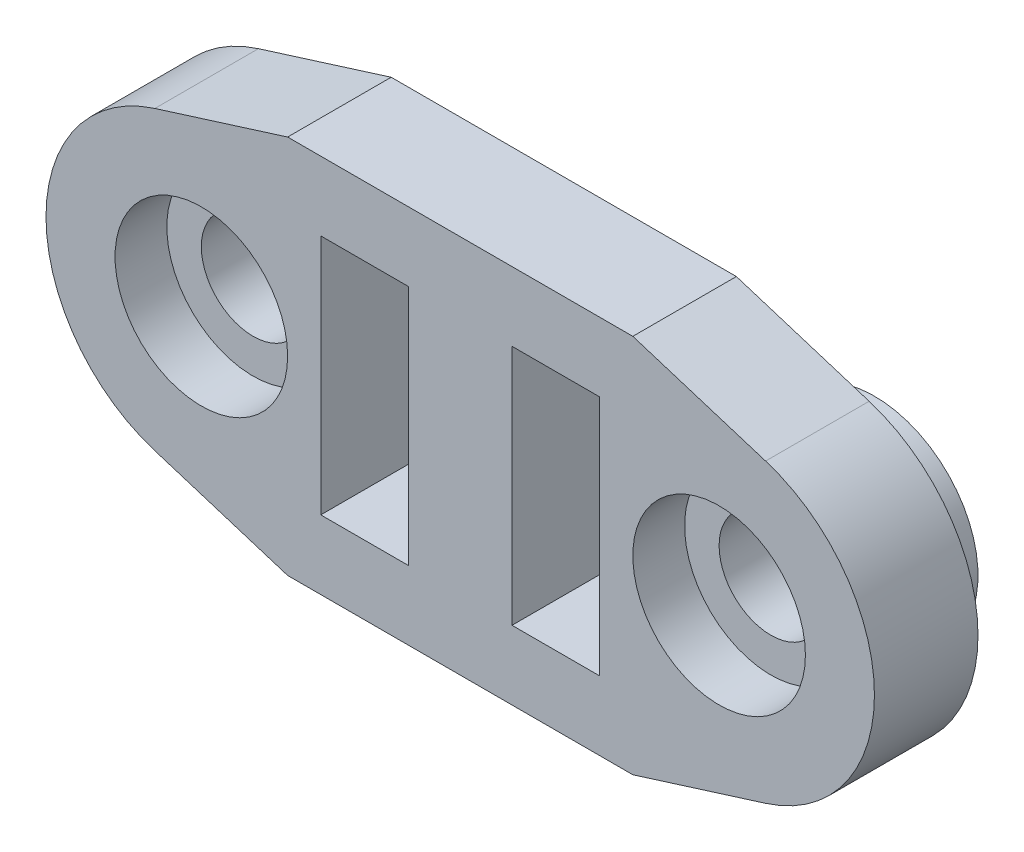
SolidWorks part; units mm, degrees
material "PLA"
ref_plane "Front Plane" through (0, 0, 0) normal (0, 0, 1) x (1, 0, 0)
ref_plane "Top Plane" through (0, 0, 0) normal (0, 1, 0) x (1, 0, 0)
ref_plane "Right Plane" through (0, 0, 0) normal (1, 0, 0) x (0, 0, -1)
sketch "Sketch1" plane through (0, 0, 0) normal (0, 0, 1) x (1, 0, 0)
  line L0 (-5, 5.5) -> (5, 5.5)
  line L1 (5, 5.5) -> (8.8465, 4.2938)
  line L2 (8.8465, -4.2938) -> (5, -5.5)
  line L3 (5, -5.5) -> (-5, -5.5)
  line L4 (-5, -5.5) -> (-8.8465, -4.2938)
  line L5 (-8.8465, 4.2938) -> (-5, 5.5)
  arc A0 (8.8465, 4.2938) -> (8.8465, -4.2938) centre (7.5, 0) cw
  arc A1 (-8.8465, -4.2938) -> (-8.8465, 4.2938) centre (-7.5, 0) cw
  circle A2 centre (-7.5, 0) radius 1.5
  circle A3 centre (7.5, 0) radius 1.5
  point P11 (0, -5.5)
  dimension "D3" = 4.5
  dimension "D4" = 3
  dimension "D1" = 11
  dimension "D2" = 15
  dimension "D5" = 10
extrude "Boss-Extrude1" add sketch "Sketch1" along normal mid plane 3
sketch "Sketch2" plane through (0, 0, -1.5) normal (0, 0, -1) x (-1, 0, 0)
  circle A0 centre (-7.5, 0) radius 3
  circle A1 centre (-7.5, 0) radius 1.5
  circle A2 centre (7.5, 0) radius 3
  circle A3 centre (7.5, 0) radius 1.5
  circle A4 centre (-7.5, 0) radius 1.5 construction
  circle A5 centre (7.5, 0) radius 1.5 construction
  dimension "D1" = 6
extrude "Boss-Extrude2" add sketch "Sketch2" along normal blind 1.5
sketch "Sketch3" plane through (0, 0, 1.5) normal (0, 0, 1) x (1, 0, 0)
  circle A0 centre (-7.5, 0) radius 2.5
  circle A1 centre (7.5, 0) radius 2.5
  dimension "D1" = 5
extrude "Cut-Extrude1" cut sketch "Sketch3" against normal blind 1.5
sketch "Sketch4" plane through (0, 0, 1.5) normal (0, 0, 1) x (1, 0, 0)
  line L0 (-1.5, 0) -> (1.5, 0) construction
  line L1 (-4.04, -3.5) -> (-1.5, -3.5)
  line L2 (-4.04, -3.5) -> (-4.04, 3.5)
  line L3 (-4.04, 3.5) -> (-1.5, 3.5)
  line L4 (-1.5, -3.5) -> (-1.5, 3.5)
  line L5 (-4.04, -3.5) -> (-1.5, 3.5) construction
  line L6 (-4.04, 3.5) -> (-1.5, -3.5) construction
  line L7 (1.5, -3.5) -> (4.04, -3.5)
  line L8 (1.5, -3.5) -> (1.5, 3.5)
  line L9 (1.5, 3.5) -> (4.04, 3.5)
  line L10 (4.04, -3.5) -> (4.04, 3.5)
  line L11 (1.5, -3.5) -> (4.04, 3.5) construction
  line L12 (1.5, 3.5) -> (4.04, -3.5) construction
  point P0 (-2.77, 0)
  point P5 (2.77, 0)
  point P10 (-1.5, 0)
  point P12 (0, 0)
  dimension "D1" = 7
  dimension "D2" = 2.54
  dimension "D3" = 3
extrude "Cut-Extrude2" cut sketch "Sketch4" against normal through all
